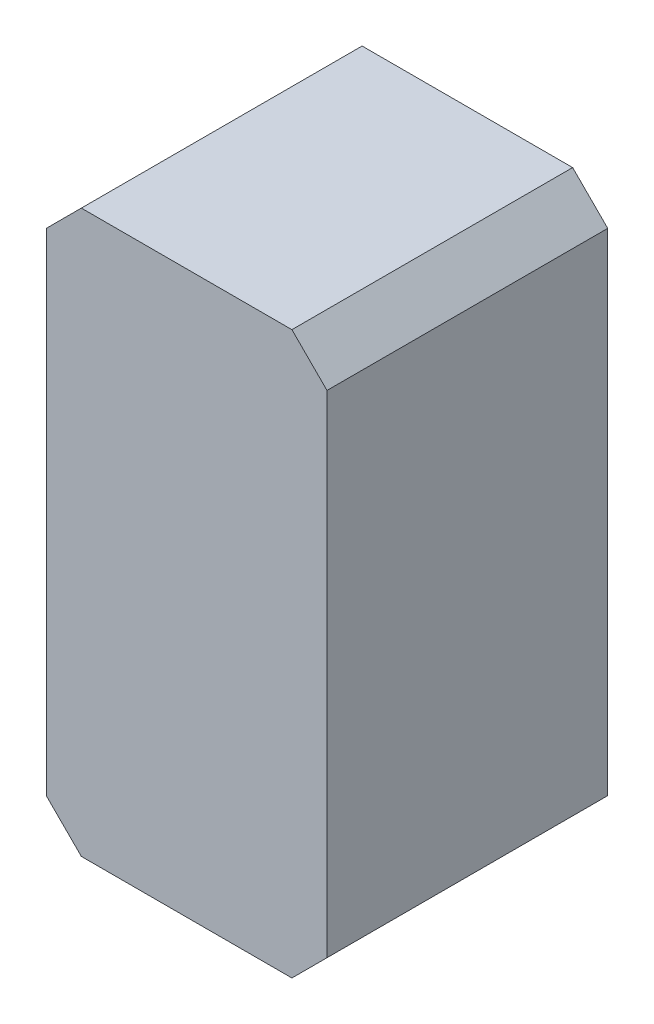
SolidWorks part; units mm, degrees
ref_plane "Front Plane" through (0, 0, 0) normal (0, 0, 1) x (1, 0, 0)
ref_plane "Top Plane" through (0, 0, 0) normal (0, 1, 0) x (1, 0, 0)
ref_plane "Right Plane" through (0, 0, 0) normal (1, 0, 0) x (0, 0, -1)
sketch "Sketch1" plane through (0, 0, 0) normal (0, 0, 1) x (1, 0, 0)
  line L1 (-2, 4) -> (2, 4)
  line L2 (-2, 4) -> (-2, -4)
  line L3 (-2, -4) -> (2, -4)
  line L4 (2, 4) -> (2, -4)
  line L5 (-2, 4) -> (2, -4) construction
  line L6 (-2, -4) -> (2, 4) construction
  point P0 (0, 0)
  dimension "D1" = 4
  dimension "D2" = 8
extrude "Boss-Extrude1" add sketch "Sketch1" along normal blind 4
chamfer "Chamfer1" distance 0.5 distance2 0.5 4 edges at (-2, -4, 2) (2, -4, 2) (-2, 4, 2) (2, 4, 2)
